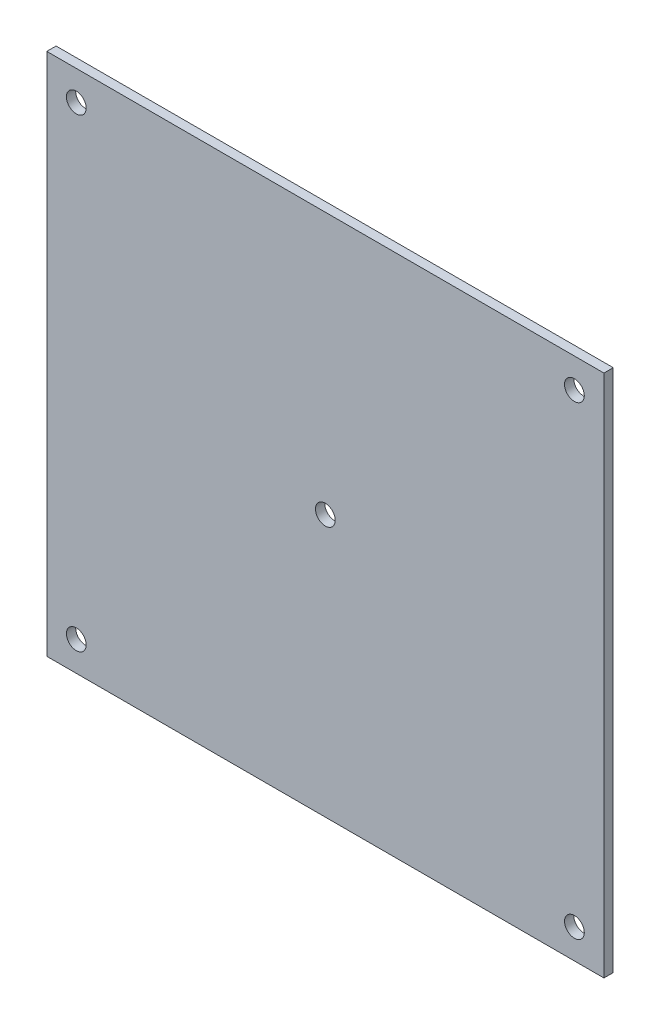
SolidWorks part; units mm, degrees
material "FR4 smeared battery v5"
ref_plane "Front Plane" through (0, 0, 0) normal (0, 0, 1) x (1, 0, 0)
ref_plane "Top Plane" through (0, 0, 0) normal (0, 1, 0) x (1, 0, 0)
ref_plane "Right Plane" through (0, 0, 0) normal (1, 0, 0) x (0, 0, -1)
sketch "Body sketch" plane through (0, 0, 0) normal (0, 0, 1) x (1, 0, 0)
  line L1 (0, 0) -> (95.89, 0)
  line L2 (0, 0) -> (0, 90.17)
  line L3 (0, 90.17) -> (95.89, 90.17)
  line L4 (95.89, 0) -> (95.89, 90.17)
extrude "Body" add sketch "Body sketch" along normal blind 1.6
sketch "Holes sketch" plane through (0, 0, 0) normal (0, 0, 1) x (1, 0, 0)
  circle A0 centre (5.08, 5.08) radius 1.7
  circle A1 centre (90.81, 5.08) radius 1.7
  circle A2 centre (5.08, 85.09) radius 1.7
  circle A3 centre (90.81, 85.09) radius 1.7
  circle A4 centre (47.945, 45.085) radius 1.7
extrude "Holes" cut sketch "Holes sketch" against normal through all and the other way through all
